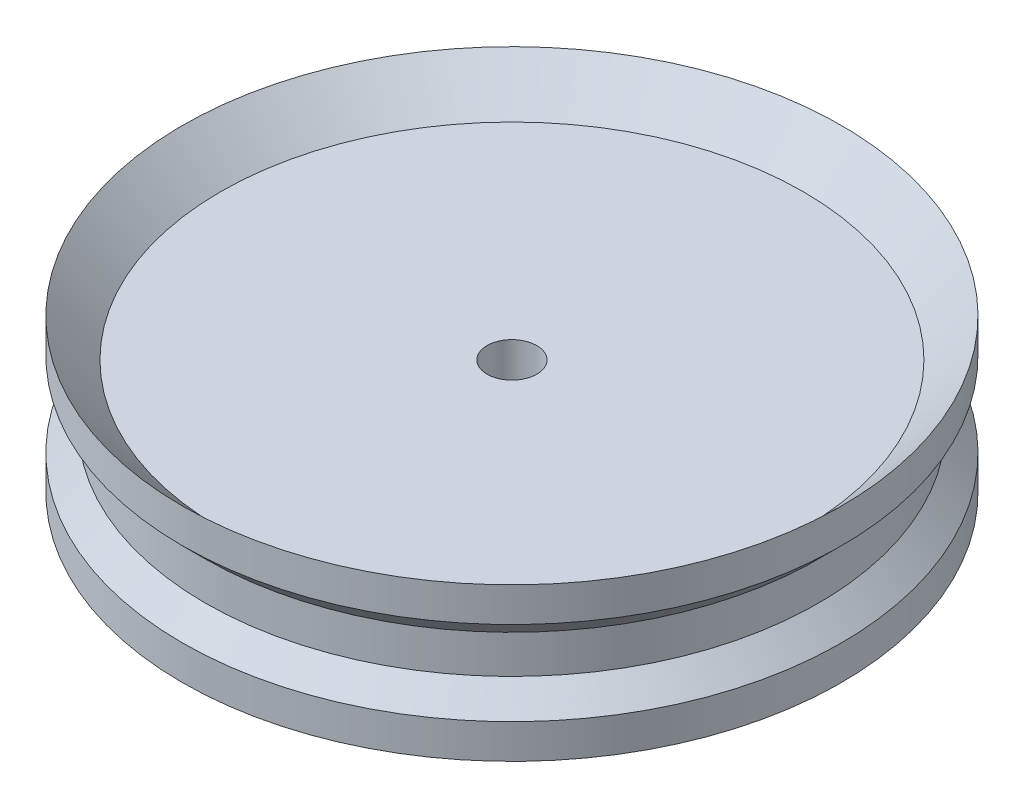
SolidWorks part; units mm, degrees
ref_plane "Front Plane" through (0, 0, 0) normal (0, 0, 1) x (1, 0, 0)
ref_plane "Top Plane" through (0, 0, 0) normal (0, 1, 0) x (1, 0, 0)
ref_plane "Right Plane" through (0, 0, 0) normal (1, 0, 0) x (0, 0, -1)
sketch "Sketch1" plane through (0, 0, 0) normal (0, 1, 0) x (1, 0, 0)
  line L0 (0, 38.1) -> (0, -38.1) construction
  circle A0 centre (0, 0) radius 38.1
  dimension "D1" = 76.2
sketch "Sketch2" plane through (0, 0, 0) normal (1, 0, 0) x (0, 0, -1)
  line L0 (0, 0) -> (-38.1, 0) construction
  line L5 (38.1, 0) -> (-38.1, 0) construction
  line L6 (38.1, 0) -> (-38.1, 0) construction
  line L7 (-38.1, 0) -> (-38.1, 5) construction
  line L8 (-38.1, 5) -> (-43.1, 10)
  line L9 (-43.1, 10) -> (-43.1, 5.5)
  line L10 (-43.1, 5.5) -> (-40.1, 2.5)
  line L11 (-40.1, 2.5) -> (-40.1, -2.5)
  line L12 (-40.1, -2.5) -> (-43.1, -5.5)
  line L13 (-43.1, -5.5) -> (-43.1, -10)
  line L14 (-43.1, -10) -> (-38.1, -5)
  line L15 (-38.1, -5) -> (-38.1, 0) construction
  line L16 (0, 0) -> (0, -5)
  line L17 (0, -5) -> (-38.1, -5)
  line L18 (-38.1, 5) -> (0, 5)
  line L19 (0, 5) -> (0, 0)
  point P2 (-38.1, 0)
  point P11 (-38.1, 0)
  point P17 (-38.1, 0)
  point P18 (0, 0)
  dimension "D1" = 5
  dimension "D2" = 5
  dimension "D3" = 3
  dimension "D4" = 10
  dimension "D5" = 38.1
sweep "Sweep1" add profiles "Sketch2" path "Sketch1"
sketch "Sketch6" plane through (0, -5, 0) normal (0, -1, 0) x (-1, 0, 0)
  circle A0 centre (0, 0) radius 3.25
  dimension "D1" = 6.5
extrude "Cut-Extrude1" cut sketch "Sketch6" against normal through all both and the other way through all
equation "\"Circle_dia\"=76.2"
equation "\"D1@Sketch1\"=\"Circle_dia\""
equation "\"D5@Sketch2\"=\"Circle_dia\"/2"
